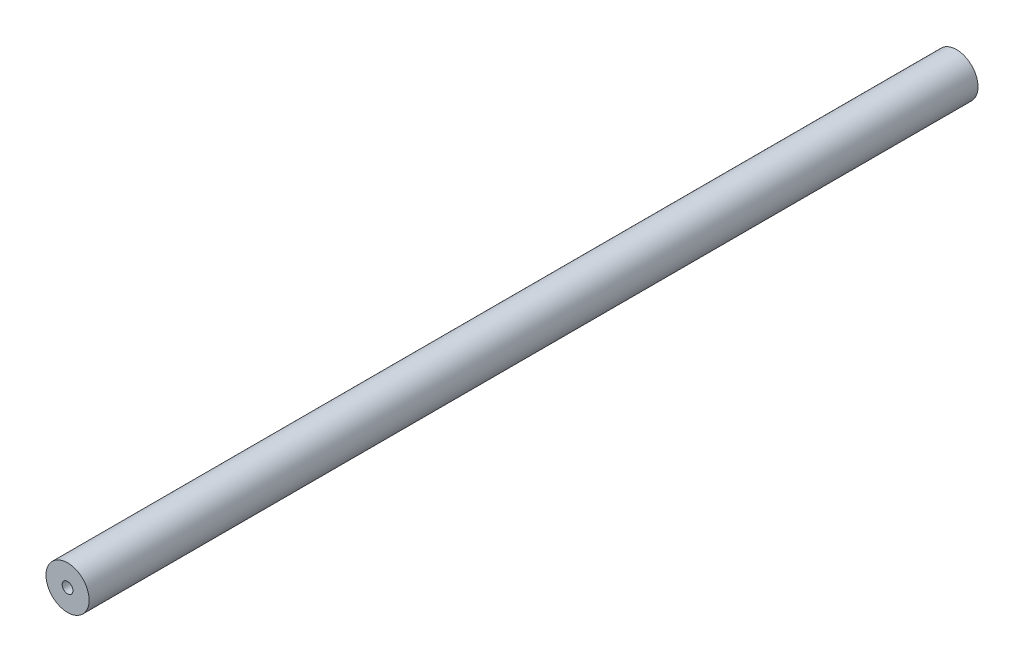
SolidWorks part; units mm, degrees
material "Oak"
ref_plane "Front Plane" through (0, 0, 0) normal (0, 0, 1) x (1, 0, 0)
ref_plane "Top Plane" through (0, 0, 0) normal (0, 1, 0) x (1, 0, 0)
ref_plane "Right Plane" through (0, 0, 0) normal (1, 0, 0) x (0, 0, -1)
sketch "Sketch1" plane through (0, 0, 0) normal (0, 0, 1) x (1, 0, 0)
  circle A0 centre (0, 0) radius 8
  dimension "D1" = 16
extrude "Boss-Extrude1" add sketch "Sketch1" along normal blind 330
sketch "Sketch2" plane through (0, 0, 330) normal (0, 0, 1) x (1, 0, 0)
  circle A0 centre (0, 0) radius 2
  dimension "D1" = 4
extrude "Cut-Extrude1" cut sketch "Sketch2" against normal through all
